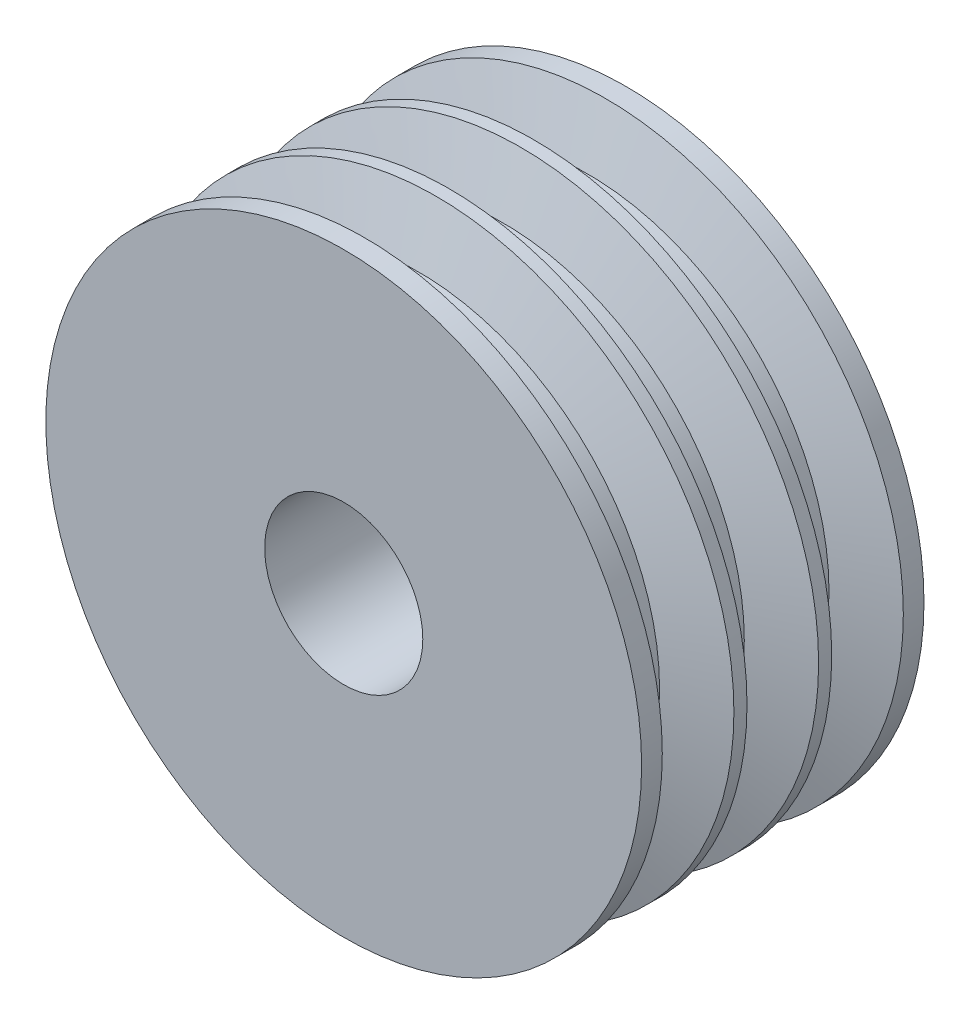
SolidWorks part; units mm, degrees
ref_plane "前视基准面" through (0, 0, 0) normal (0, 0, 1) x (1, 0, 0)
ref_plane "上视基准面" through (0, 0, 0) normal (0, 1, 0) x (1, 0, 0)
ref_plane "右视基准面" through (0, 0, 0) normal (1, 0, 0) x (0, 0, -1)
other "Configuration Table"
sketch "草图2" plane through (0, 0, 0) normal (1, 0, 0) x (0, 0, -1)
  line L0 (0, 0) -> (50, 0) construction
  line L1 (0, 0) -> (0, 14) construction
  line L2 (0, 52.75) -> (3.6592, 52.75)
  line L3 (0, 14) -> (50, 14)
  line L4 (50, 14) -> (50, 52.75)
  line L5 (0, 52.75) -> (0, 14)
  line L6 (6.7407, 42.671) -> (13.2593, 42.671)
  line L7 (16.3408, 52.75) -> (18.6592, 52.75)
  line L8 (6.7407, 42.671) -> (3.6592, 52.75)
  line L9 (21.7407, 42.671) -> (18.6592, 52.75)
  line L10 (13.2593, 42.671) -> (16.3408, 52.75)
  line L11 (21.7407, 42.671) -> (28.2593, 42.671)
  line L12 (28.2593, 42.671) -> (31.3408, 52.75)
  line L13 (36.7407, 42.671) -> (33.6592, 52.75)
  line L14 (36.7407, 42.671) -> (43.2593, 42.671)
  line L15 (43.2593, 42.671) -> (46.3408, 52.75)
  line L16 (31.3408, 52.75) -> (33.6592, 52.75)
  line L17 (46.3408, 52.75) -> (50, 52.75)
revolve "旋转2" add sketch "草图2" angle 360 about L0
